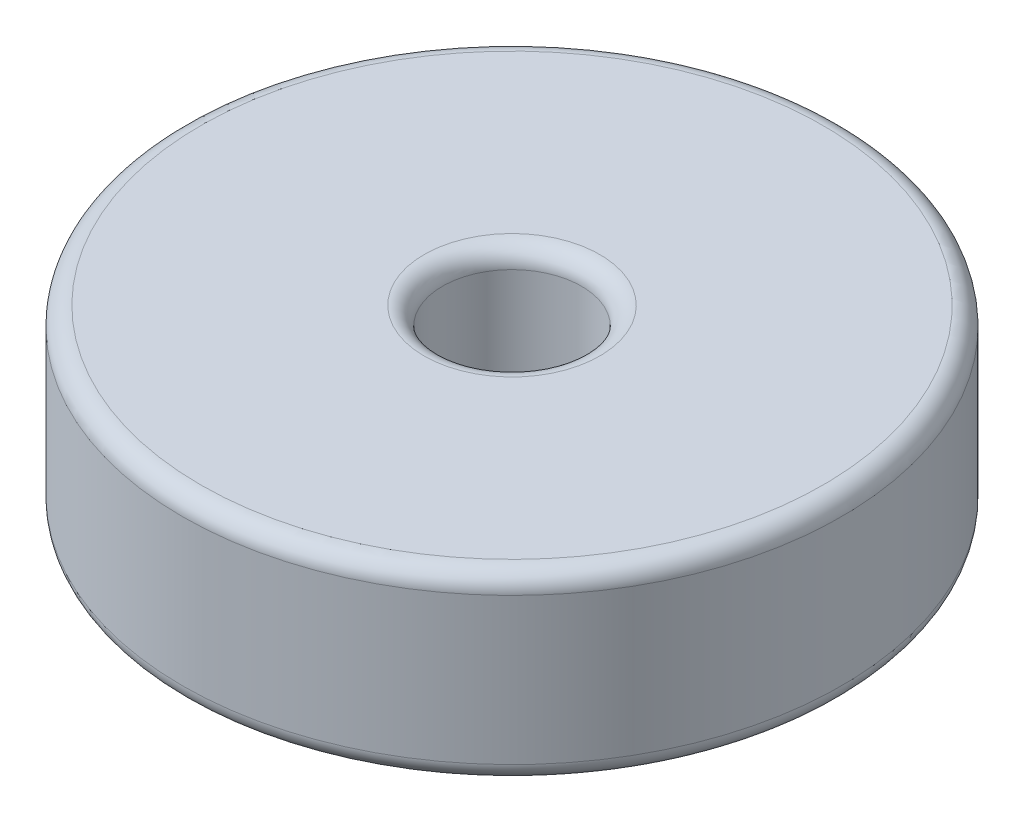
SolidWorks part; units mm, degrees
ref_plane "Front Plane" through (0, 0, 0) normal (0, 0, 1) x (1, 0, 0)
ref_plane "Top Plane" through (0, 0, 0) normal (0, 1, 0) x (1, 0, 0)
ref_plane "Right Plane" through (0, 0, 0) normal (1, 0, 0) x (0, 0, -1)
sketch "Sketch1" plane through (0, 0, 0) normal (0, 1, 0) x (1, 0, 0)
  circle A0 centre (0, 0) radius 11.43
  circle A1 centre (0, 0) radius 2.413
  dimension "D2" = 22.86
  dimension "D1" = 4.826
extrude "Boss-Extrude1" add sketch "Sketch1" along normal mid plane 6.35
fillet "Fillet1" radius 0.635 4 edges at (0, -3.175, 2.413) (0, -3.175, 11.43) (0, 3.175, 2.413) (0, 3.175, 11.43)
